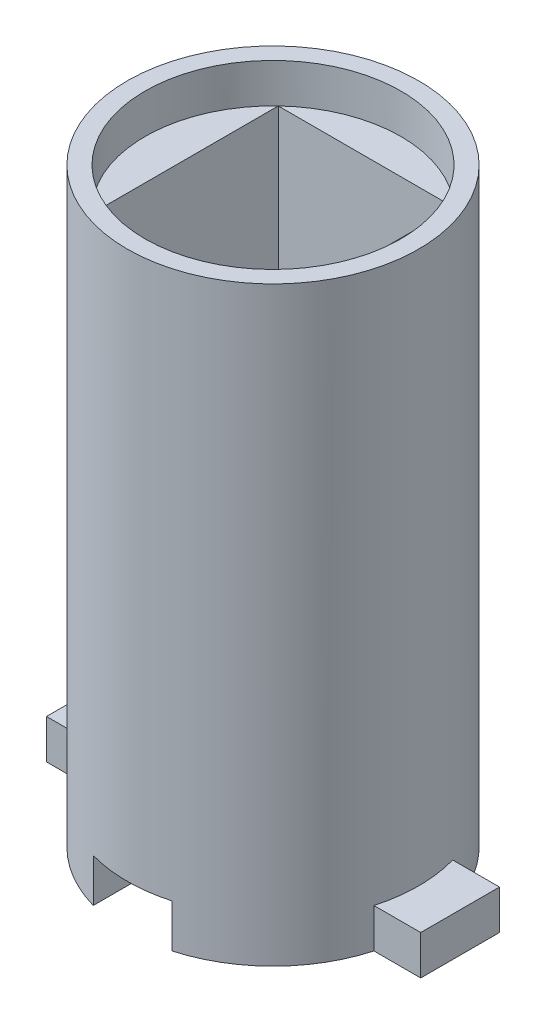
SolidWorks part; units mm, degrees
ref_plane "Front Plane" through (0, 0, 0) normal (0, 0, 1) x (1, 0, 0)
ref_plane "Top Plane" through (0, 0, 0) normal (0, 1, 0) x (1, 0, 0)
ref_plane "Right Plane" through (0, 0, 0) normal (1, 0, 0) x (0, 0, -1)
sketch "Sketch1" plane through (0, 0, 0) normal (0, 1, 0) x (1, 0, 0)
  circle A0 centre (0, 0) radius 37
  dimension "D1" = 74
extrude "Boss-Extrude1" add sketch "Sketch1" along normal blind 150
sketch "Sketch2" plane through (0, 150, 0) normal (0, 1, 0) x (1, 0, 0)
  line L1 (-11.5, 11.5) -> (11.5, 11.5)
  line L2 (-11.5, 11.5) -> (-11.5, -11.5)
  line L3 (-11.5, -11.5) -> (11.5, -11.5)
  line L4 (11.5, 11.5) -> (11.5, -11.5)
  line L5 (-11.5, 11.5) -> (11.5, -11.5) construction
  line L6 (-11.5, -11.5) -> (11.5, 11.5) construction
  point P0 (0, 0)
  dimension "D1" = 23
  dimension "D2" = 23
extrude "Cut-Extrude1" cut sketch "Sketch2" against normal blind 150
sketch "Sketch3" plane through (0, 0, 0) normal (0, -1, 0) x (1, 0, 0)
  line L1 (-21.5, 21.5) -> (21.5, 21.5)
  line L2 (-21.5, 21.5) -> (-21.5, -21.5)
  line L3 (-21.5, -21.5) -> (21.5, -21.5)
  line L4 (21.5, 21.5) -> (21.5, -21.5)
  line L5 (-21.5, 21.5) -> (21.5, -21.5) construction
  line L6 (-21.5, -21.5) -> (21.5, 21.5) construction
  point P0 (0, 0)
  dimension "D1" = 43
  dimension "D2" = 43
extrude "Cut-Extrude2" cut sketch "Sketch3" against normal blind 36
chamfer "Chamfer1" distance 5 angle 45 4 edges at (21.5, 18, 21.5) (-21.5, 18, 21.5) (-21.5, 18, -21.5) (21.5, 18, -21.5)
sketch "Sketch5" plane through (0, 150, 0) normal (0, 1, 0) x (1, 0, 0)
  circle A0 centre (0, 0) radius 32.5
  dimension "D1" = 65
extrude "Cut-Extrude3" cut sketch "Sketch5" against normal blind 10
sketch "Sketch11" plane through (0, 140, 0) normal (0, 1, 0) x (1, 0, 0)
  line L1 (-22.3036, 23.6389) -> (22.3036, 23.6389)
  line L2 (-22.3036, 23.6389) -> (-22.3036, -23.6389)
  line L3 (-22.3036, -23.6389) -> (22.3036, -23.6389)
  line L4 (22.3036, 23.6389) -> (22.3036, -23.6389)
  line L5 (-22.3036, 23.6389) -> (22.3036, -23.6389) construction
  line L6 (-22.3036, -23.6389) -> (22.3036, 23.6389) construction
  circle A0 centre (0, 0) radius 32.5 construction
  point P0 (0, 0)
extrude "Cut-Extrude7" cut sketch "Sketch11" against normal blind 104
sketch "Sketch12" plane through (0, 0, 0) normal (0, -1, 0) x (1, 0, 0)
  line L0 (21.5, -16.5) -> (21.5, 16.5) construction
  line L1 (-47.5, 10) -> (-21.5, 10)
  line L2 (-47.5, 10) -> (-47.5, -10)
  line L3 (-47.5, -10) -> (-21.5, -10)
  line L4 (47.5, 10) -> (47.5, -10)
  line L5 (-47.5, 10) -> (-21.5, 4.5263) construction
  line L6 (-47.5, -10) -> (-21.5, -4.5263) construction
  line L8 (-21.5, 10) -> (-21.5, -10)
  line L10 (21.5, 10) -> (21.5, -10)
  line L13 (21.5, 10) -> (47.5, 10)
  line L14 (21.5, -4.5263) -> (47.5, -10) construction
  line L15 (21.5, 4.5263) -> (47.5, 10) construction
  line L16 (21.5, -10) -> (47.5, -10)
  point P0 (0, 0)
  point P6 (0, 0)
  dimension "D1" = 95
  dimension "D2" = 20
extrude "Boss-Extrude2" add sketch "Sketch12" against normal blind 10
sketch "Sketch13" plane through (0, 0, 0) normal (0, -1, 0) x (1, 0, 0)
  line L0 (0, 0) -> (0, 37) construction
  line L1 (16.5, 21.5) -> (-16.5, 21.5) construction
  line L2 (-10, 52.5) -> (10, 52.5)
  line L3 (-10, 52.5) -> (-10, 21.5)
  line L4 (-10, 21.5) -> (10, 21.5)
  line L5 (10, 52.5) -> (10, 21.5)
  line L6 (-10, 52.5) -> (10, 21.5) construction
  line L7 (-10, 21.5) -> (10, 52.5) construction
  arc A0 (35.623, 10) -> (-35.623, 10) centre (0, 0) ccw construction
  dimension "D1" = 20
extrude "Cut-Extrude8" cut sketch "Sketch13" against normal blind 11
